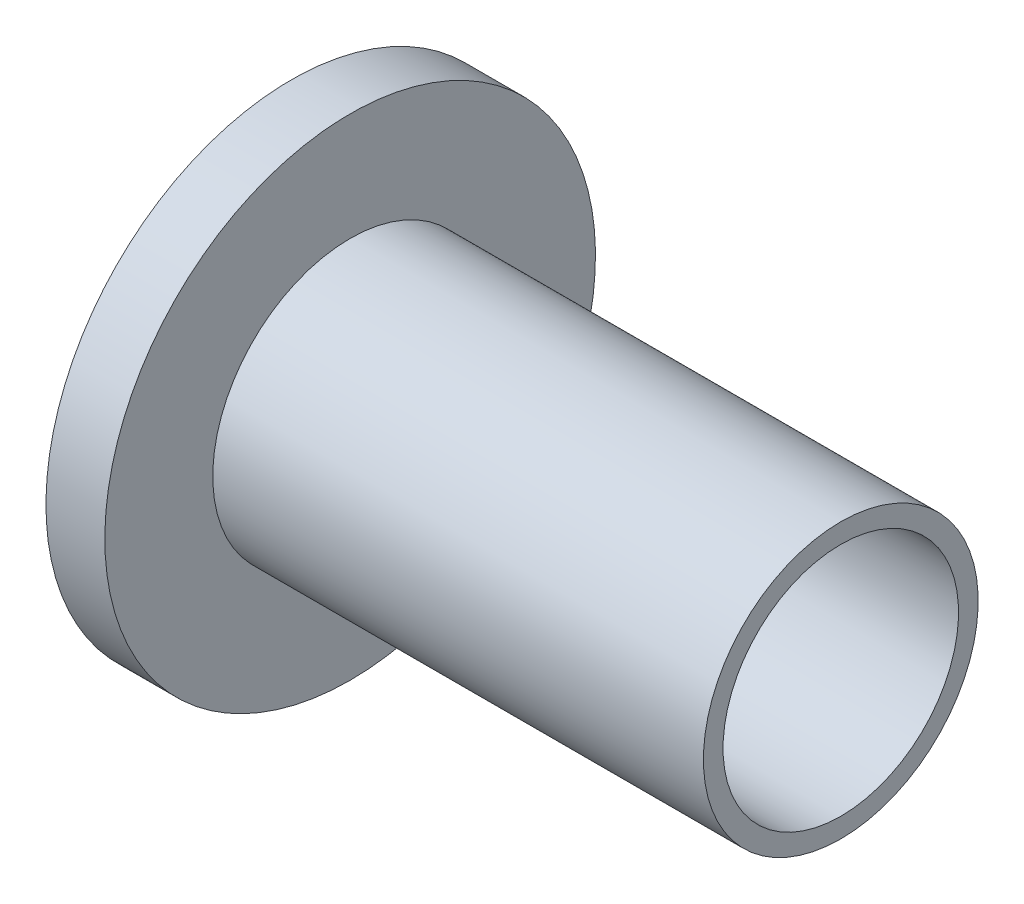
SolidWorks part; units mm, degrees
ref_plane "Front Plane" through (0, 0, 0) normal (0, 0, 1) x (1, 0, 0)
ref_plane "Top Plane" through (0, 0, 0) normal (0, 1, 0) x (1, 0, 0)
ref_plane "Right Plane" through (0, 0, 0) normal (1, 0, 0) x (0, 0, -1)
sketch "Sketch2" plane through (0, 0, 0) normal (0, 0, 1) x (1, 0, 0)
  line L0 (-53.0183, 0) -> (53.0183, 0) construction
  line L1 (0, -40.0686) -> (0, 40.0686) construction
sketch "Sketch1" plane through (0, 0, 0) normal (0, 0, 1) x (1, 0, 0)
  line L0 (-64.9001, 0) -> (64.9001, 0) construction
  line L1 (0, 25) -> (0, 10)
  line L4 (19, 12) -> (56, 12)
  line L5 (56, 12) -> (56, 14)
  line L6 (56, 14) -> (6, 14)
  line L7 (6, 14) -> (6, 25)
  line L8 (6, 25) -> (0, 25)
  line L13 (0, 10) -> (19, 10)
  line L14 (0, 10) -> (0, 0) construction
  line L15 (19, 12) -> (19, 10)
  point P3 (0, 0)
  point P5 (0, 0)
  point P6 (3, 25)
  dimension "D1" = 24
  dimension "D2" = 28
  dimension "D3" = 13
  dimension "D4" = 50
  dimension "D5" = 6
  dimension "D6" = 50
  dimension "D10" = 20
revolve "Revolve1" add sketch "Sketch1" angle 360 about L0
sketch "Sketch4" plane through (0, 0, 0) normal (0, 1, 0) x (1, 0, 0)
  line L0 (-53.0183, 0) -> (53.0183, 0) construction
  line L1 (19, -6.5) -> (11, -6.5)
  line L2 (19, -6.5) -> (19, 6.5)
  line L3 (19, 6.5) -> (11, 6.5)
  line L4 (11, -6.5) -> (11, 6.5)
  point P4 (11, 0)
  dimension "D1" = 8
  dimension "D2" = 13
extrude "Cut-Extrude1" cut sketch "Sketch4" against normal up to next
